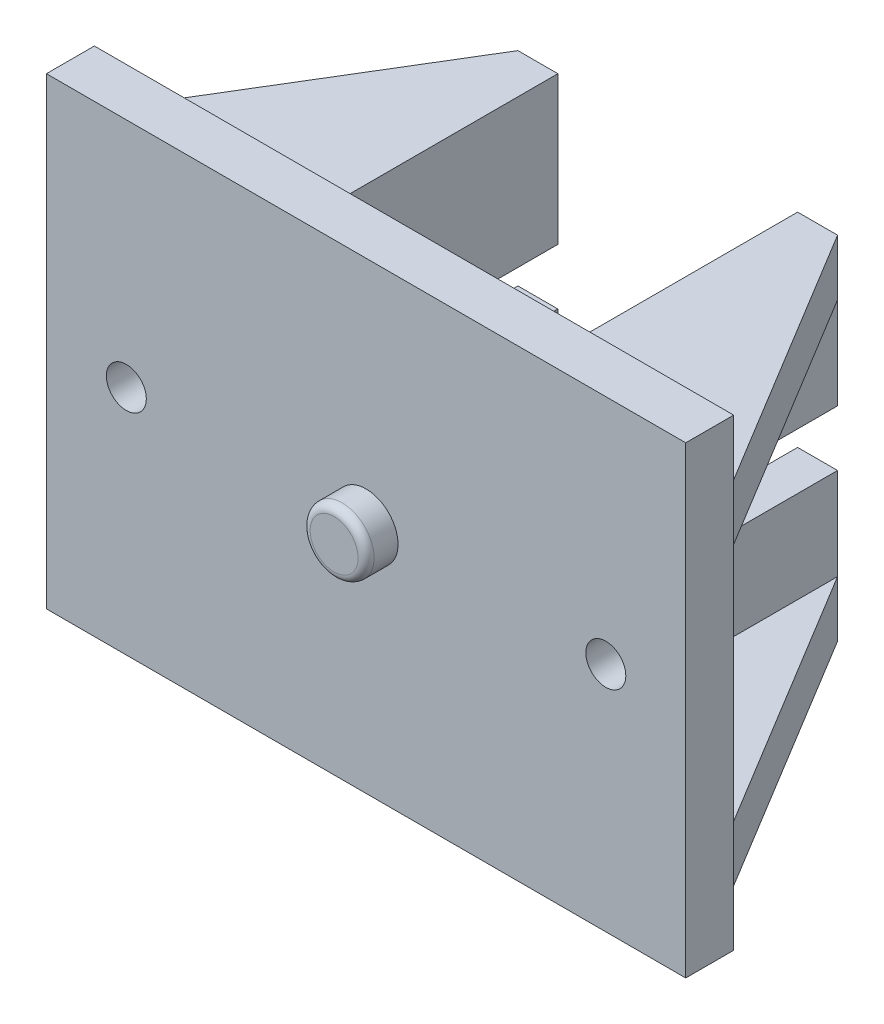
SolidWorks part; units mm, degrees
ref_plane "정면" through (0, 0, 0) normal (0, 0, 1) x (1, 0, 0)
ref_plane "윗면" through (0, 0, 0) normal (0, 1, 0) x (1, 0, 0)
ref_plane "우측면" through (0, 0, 0) normal (1, 0, 0) x (0, 0, -1)
sketch "스케치2" plane through (0, 0, 0) normal (0, 0, 1) x (1, 0, 0)
  line L0 (55, 0) -> (-55, 0) construction
  line L1 (-40, -29) -> (40, -29)
  line L2 (-40, -29) -> (-40, 29)
  line L3 (-40, 29) -> (40, 29)
  line L4 (40, -29) -> (40, 29)
  line L5 (-40, -29) -> (40, 29) construction
  line L6 (-40, 29) -> (40, -29) construction
  circle A0 centre (-30, 0) radius 2.5
  circle A1 centre (30, 0) radius 2.5
  point P0 (0, 0)
  dimension "D3" = 10
  dimension "D4" = 60
  dimension "D1" = 80
  dimension "D2" = 58
extrude "보스-돌출1" add sketch "스케치2" along normal blind 6
sketch "스케치3" plane through (0, 0, 0) normal (0, 0, -1) x (-1, 0, 0)
  line L1 (-20, 22) -> (-15, 22)
  line L2 (-20, 22) -> (-20, -22)
  line L3 (-20, -22) -> (-15, -22)
  line L4 (-15, 22) -> (-15, -22)
  line L6 (-40, -29) -> (-40, 29) construction
  line L7 (15, 22) -> (20, 22)
  line L8 (15, 22) -> (15, -22)
  line L9 (15, -22) -> (20, -22)
  line L10 (20, 22) -> (20, -22)
  line L11 (55, 0) -> (-55, 0) construction
  point P4 (20, 0)
  point P7 (-20, 0)
  dimension "D1" = 30
  dimension "D2" = 5
  dimension "D3" = 5
  dimension "D4" = 20
  dimension "D5" = 44
  dimension "D6" = 44
extrude "보스-돌출2" add sketch "스케치3" along normal blind 33
sketch "스케치11" plane through (20, 0, 0) normal (1, 0, 0) x (0, 0, -1)
  line L0 (33, 22) -> (33, -22) construction
  line L1 (33, -3.5) -> (11, -3.5)
  line L2 (33, -3.5) -> (33, 3.5)
  line L3 (33, 3.5) -> (11, 3.5)
  line L4 (8, -0.5) -> (8, 0.5)
  line L5 (55, 0) -> (-55, 0) construction
  arc A0 (11, -3.5) -> (8, -0.5) centre (11, -0.5) cw
  arc A1 (11, 3.5) -> (8, 0.5) centre (11, 0.5) ccw
  point P8 (33, 0)
  dimension "D2" = 3
  dimension "D1" = 7
  dimension "D3" = 25
extrude "컷-돌출1" cut sketch "스케치11" against normal through all both and the other way through all
sketch "스케치12" plane through (0, 0, 6) normal (0, 0, 1) x (1, 0, 0)
  circle A0 centre (0, 0) radius 4
extrude "보스-돌출3" add sketch "스케치12" along normal blind 4
ref_plane "평면1" through (0, 15, 0) normal (0, 1, 0) x (1, 0, 0)
ref_plane "평면2" through (0, -15, 0) normal (0, 1, 0) x (1, 0, 0)
sketch "스케치13" plane through (0, 15, 0) normal (0, 1, 0) x (1, 0, 0)
  line L0 (-20, 33) -> (-40, 0)
sketch "스케치16" plane through (0, -15, 0) normal (0, 1, 0) x (1, 0, 0)
  line L0 (-20, 33) -> (-40, 0)
rib "보강대10" sketch "스케치13" sketch "스케치13" thickness 7 parameters "D1"=7
rib "보강대12" sketch "스케치16" sketch "스케치16" thickness 7 extrusion direction parallel to sketch draft on no parameters "D1"=7
mirror "대칭 복사1" about plane through (0, 0, 0) normal (1, 0, 0) of "보강대10"
mirror "대칭 복사2" about plane through (0, 0, 0) normal (1, 0, 0) of "보강대12"
fillet "필렛2" radius 1 1 edges at (4, 0, 10)
